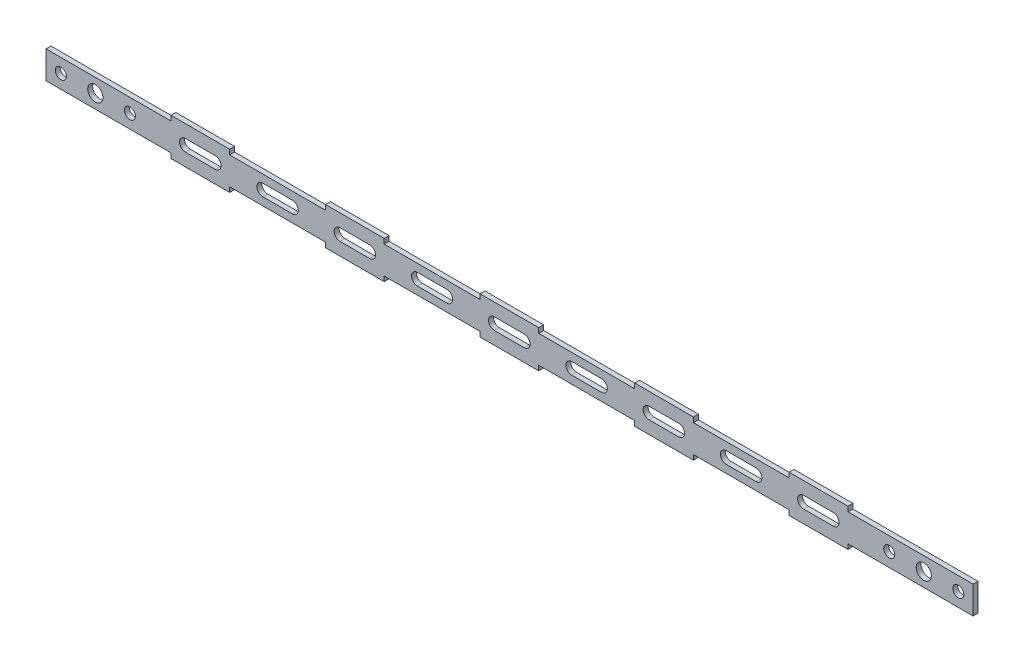
SolidWorks part; units mm, degrees
material "Acrylic (Medium-high impact)"
ref_plane "Plan de face" through (0, 0, 0) normal (0, 0, 1) x (1, 0, 0)
ref_plane "Plan de dessus" through (0, 0, 0) normal (0, 1, 0) x (1, 0, 0)
ref_plane "Plan de droite" through (0, 0, 0) normal (1, 0, 0) x (0, 0, -1)
sketch "Sketch1" plane through (0, 0, 0) normal (0, 0, 1) x (1, 0, 0)
  line L6 (298.45, -8.89) -> (-298.45, -8.89)
  line L9 (298.45, -8.89) -> (298.45, 8.89)
  line L10 (298.45, 8.89) -> (-298.45, 8.89)
  line L12 (-298.45, -8.89) -> (-298.45, 8.89)
  line L13 (298.45, -8.89) -> (-298.45, 8.89) construction
  line L14 (298.45, 8.89) -> (-298.45, -8.89) construction
  point P0 (0, 0)
  dimension "D1" = 596.9
  dimension "D2" = 17.78
extrude "Boss-Extrude1" add sketch "Sketch1" along normal blind 3.175
sketch "Sketch3" plane through (0, 8.89, 0) normal (0, 1, 0) x (1, 0, 0)
  line L5 (298.45, 0) -> (-298.45, 0) construction
  line L6 (-218.0167, 0) -> (-180.1707, 0)
  line L7 (-218.0167, 0) -> (-218.0167, -3.175)
  line L8 (-218.0167, -3.175) -> (-180.1707, -3.175)
  line L9 (-180.1707, 0) -> (-180.1707, -3.175)
  line L10 (298.45, -3.175) -> (-298.45, -3.175) construction
  line L12 (-118.5333, 0) -> (-80.6873, 0)
  line L13 (-118.5333, 0) -> (-118.5333, -3.175)
  line L14 (-118.5333, -3.175) -> (-80.6873, -3.175)
  line L15 (-80.6873, 0) -> (-80.6873, -3.175)
  line L16 (-19.05, 0) -> (18.796, 0)
  line L17 (-19.05, 0) -> (-19.05, -3.175)
  line L18 (-19.05, -3.175) -> (18.796, -3.175)
  line L19 (18.796, 0) -> (18.796, -3.175)
  line L20 (80.5603, 0) -> (118.4063, 0)
  line L21 (80.5603, 0) -> (80.5603, -3.175)
  line L22 (80.5603, -3.175) -> (118.4063, -3.175)
  line L23 (118.4063, 0) -> (118.4063, -3.175)
  line L24 (180.0437, 0) -> (217.8897, 0)
  line L25 (180.0437, 0) -> (180.0437, -3.175)
  line L26 (180.0437, -3.175) -> (217.8897, -3.175)
  line L27 (217.8897, 0) -> (217.8897, -3.175)
  point P8 (-99.6103, 0)
  point P9 (-199.0937, 0)
  point P26 (-0.127, 0)
  point P27 (99.4833, 0)
  point P31 (198.9667, 0)
  dimension "D1" = 37.846
  dimension "D2" = 99.4833
  dimension "D3" = 37.846
  dimension "D4" = 37.846
  dimension "D5" = 37.846
  dimension "D6" = 37.846
  dimension "D7" = 99.4833
  dimension "D8" = 99.4833
  dimension "D9" = 99.4833
extrude "Boss-Extrude2" add sketch "Sketch3" along normal blind 3.175
mirror "Mirror1" about plane through (0, 0, 0) normal (0, 1, 0) of "Boss-Extrude2"
sketch "Sketch4" plane through (0, 0, 0) normal (0, 0, -1) x (-1, 0, 0)
  line L0 (-298.45, -8.89) -> (-298.45, 8.89) construction
  circle A0 centre (-288.925, 0) radius 3.556
  circle A2 centre (-244.475, 0) radius 3.556
  circle A3 centre (-266.7, 0) radius 4.8895
  dimension "D4" = 7.112
  dimension "D5" = 7.112
  dimension "D6" = 9.779
  dimension "D1" = 9.525
  dimension "D2" = 31.75
  dimension "D3" = 44.45
extrude "Cut-Extrude1" cut sketch "Sketch4" against normal through all
mirror "Mirror2" about plane through (0, 0, 0) normal (1, 0, 0) of "Cut-Extrude1"
sketch "Sketch6" plane through (0, 0, 3.175) normal (0, 0, 1) x (1, 0, 0)
  line L0 (-208.6187, 0) -> (-189.5687, 0) construction
  line L1 (-208.6187, 3.81) -> (-189.5687, 3.81)
  line L2 (-208.6187, -3.81) -> (-189.5687, -3.81)
  line L3 (-218.0167, 12.065) -> (-180.1707, 12.065) construction
  line L8 (-109.1353, 0) -> (-90.0853, 0) construction
  line L11 (-109.1353, 3.81) -> (-90.0853, 3.81)
  line L12 (-109.1353, -3.81) -> (-90.0853, -3.81)
  line L13 (-9.652, 0) -> (9.398, 0) construction
  line L14 (-9.652, 3.81) -> (9.398, 3.81)
  line L15 (-9.652, -3.81) -> (9.398, -3.81)
  line L16 (89.8313, 0) -> (108.8813, 0) construction
  line L17 (89.8313, 3.81) -> (108.8813, 3.81)
  line L18 (89.8313, -3.81) -> (108.8813, -3.81)
  line L19 (189.3147, 0) -> (208.3647, 0) construction
  line L20 (189.3147, 3.81) -> (208.3647, 3.81)
  line L21 (189.3147, -3.81) -> (208.3647, -3.81)
  line L22 (-158.877, 0) -> (-139.827, 0) construction
  line L23 (-158.877, 3.81) -> (-139.827, 3.81)
  line L24 (-158.877, -3.81) -> (-139.827, -3.81)
  line L25 (-59.3195, 0) -> (-40.4179, 0) construction
  line L26 (-59.3195, 3.81) -> (-40.4179, 3.81)
  line L27 (-59.3195, -3.81) -> (-40.4179, -3.81)
  line L28 (40.0897, 0) -> (59.1397, 0) construction
  line L29 (40.0897, 3.81) -> (59.1397, 3.81)
  line L30 (40.0897, -3.81) -> (59.1397, -3.81)
  line L31 (139.573, 0) -> (158.623, 0) construction
  line L32 (139.573, 3.81) -> (158.623, 3.81)
  line L33 (139.573, -3.81) -> (158.623, -3.81)
  line L34 (-180.1707, -8.89) -> (-118.5333, -8.89) construction
  line L35 (-199.0937, 0) -> (-149.352, 0) construction
  line L36 (-149.352, 0) -> (-99.6103, 0) construction
  line L37 (-99.6103, 0) -> (-49.8687, 0) construction
  line L38 (-49.8687, 0) -> (-0.127, 0) construction
  line L39 (-0.127, 0) -> (49.6147, 0) construction
  line L40 (49.6147, 0) -> (99.3563, 0) construction
  line L41 (99.3563, 0) -> (149.098, 0) construction
  line L42 (149.098, 0) -> (198.8397, 0) construction
  arc A0 (-208.6187, 3.81) -> (-208.6187, -3.81) centre (-208.6187, 0) ccw
  arc A1 (-189.5687, -3.81) -> (-189.5687, 3.81) centre (-189.5687, 0) ccw
  arc A8 (-109.1353, 3.81) -> (-109.1353, -3.81) centre (-109.1353, 0) ccw
  arc A9 (-90.0853, -3.81) -> (-90.0853, 3.81) centre (-90.0853, 0) ccw
  arc A10 (-9.652, 3.81) -> (-9.652, -3.81) centre (-9.652, 0) ccw
  arc A11 (9.398, -3.81) -> (9.398, 3.81) centre (9.398, 0) ccw
  arc A12 (89.8313, 3.81) -> (89.8313, -3.81) centre (89.8313, 0) ccw
  arc A13 (108.8813, -3.81) -> (108.8813, 3.81) centre (108.8813, 0) ccw
  arc A14 (189.3147, 3.81) -> (189.3147, -3.81) centre (189.3147, 0) ccw
  arc A15 (208.3647, -3.81) -> (208.3647, 3.81) centre (208.3647, 0) ccw
  arc A16 (-158.877, 3.81) -> (-158.877, -3.81) centre (-158.877, 0) ccw
  arc A17 (-139.827, -3.81) -> (-139.827, 3.81) centre (-139.827, 0) ccw
  arc A18 (-59.3195, 3.81) -> (-59.3195, -3.81) centre (-59.3195, 0) ccw
  arc A19 (-40.4179, -3.81) -> (-40.4179, 3.81) centre (-40.4179, 0) ccw
  arc A20 (40.0897, 3.81) -> (40.0897, -3.81) centre (40.0897, 0) ccw
  arc A21 (59.1397, -3.81) -> (59.1397, 3.81) centre (59.1397, 0) ccw
  arc A22 (139.573, 3.81) -> (139.573, -3.81) centre (139.573, 0) ccw
  arc A23 (158.623, -3.81) -> (158.623, 3.81) centre (158.623, 0) ccw
  point P2 (-199.0937, 0)
  point P7 (0, 0)
  point P12 (-199.0937, 12.065)
  point P14 (-99.6103, 0)
  point P21 (-0.127, 0)
  point P28 (99.3563, 0)
  point P35 (198.8397, 0)
  point P44 (-149.352, 0)
  point P51 (-49.8687, 0)
  point P58 (49.6147, 0)
  point P65 (149.098, 0)
  point P72 (-149.352, -8.89)
  point P82 (-53.2571, 20.5814)
  dimension "D1" = 7.62
  dimension "D2" = 19.05
  dimension "D3" = 49.7417
  dimension "D4" = 19.05
  dimension "D5" = 19.05
  dimension "D6" = 9.4508
  dimension "D7" = 19.05
  dimension "D8" = 19.05
  dimension "D9" = 19.05
  dimension "D10" = 19.05
  dimension "D11" = 19.05
  dimension "D12" = 7.62
  dimension "D13" = 7.62
  dimension "D14" = 7.62
  dimension "D15" = 7.62
  dimension "D16" = 7.62
  dimension "D17" = 7.62
  dimension "D18" = 7.62
  dimension "D19" = 7.62
extrude "Cut-Extrude3" cut sketch "Sketch6" against normal through all
